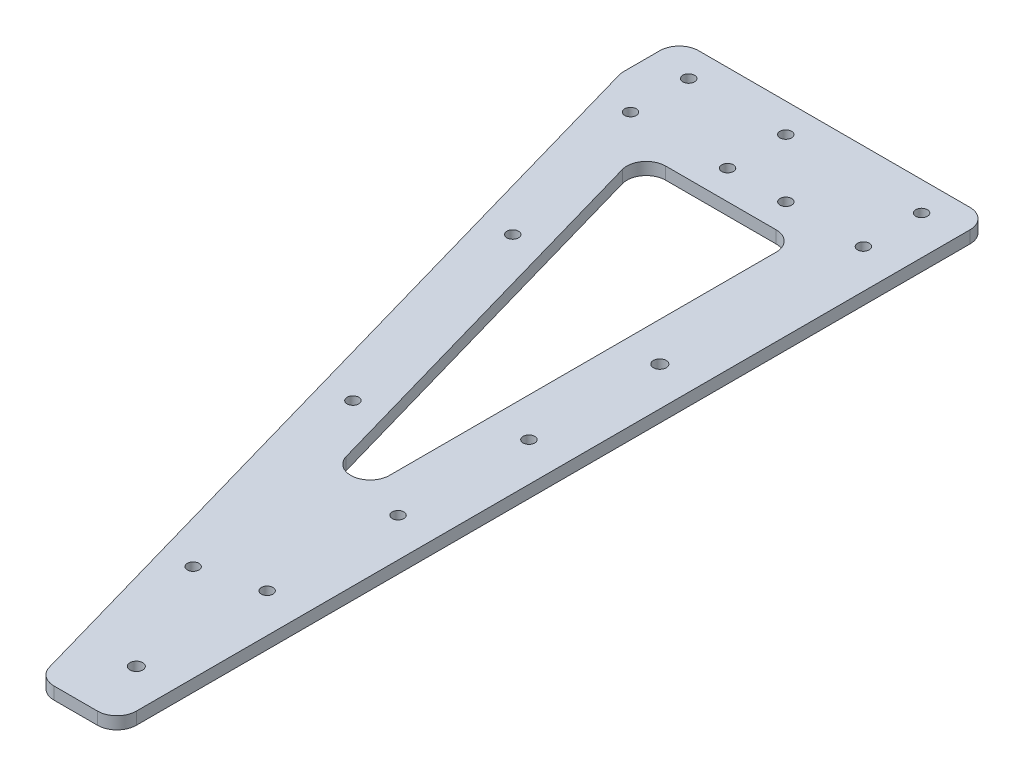
SolidWorks part; units mm, degrees
ref_plane "Front" through (0, 0, 0) normal (0, 0, 1) x (1, 0, 0)
ref_plane "Top" through (0, 0, 0) normal (0, 1, 0) x (1, 0, 0)
ref_plane "Right" through (0, 0, 0) normal (1, 0, 0) x (0, 0, -1)
sketch "Sketch1" plane through (0, 0, 0) normal (0, 1, 0) x (1, 0, 0)
  line L0 (-20, -210) -> (-80, 0)
  line L1 (0, 0) -> (-20, 0)
  line L2 (0, 0) -> (0, -210)
  line L3 (0, -210) -> (-20, -210)
  line L4 (-20, 0) -> (-20, -210)
  line L5 (-80, 0) -> (-20, 0)
  line L6 (-10, -210) -> (-10, -195)
  line L7 (-10, -195) -> (-10, -60)
  line L8 (-12.7886, -207.9396) -> (-70.057, -7.5)
  line L9 (-70.057, -7.5) -> (-20, -7.5)
  line L10 (-5.5771, -205.8792) -> (-60.1141, -15)
  line L11 (-60.1141, -15) -> (-20, -15)
  circle A0 centre (-10, -195) radius 1.65
  circle A1 centre (-10, -60) radius 1.65
  circle A2 centre (-70.057, -7.5) radius 1.5
  circle A3 centre (-45.0285, -7.5) radius 1.5
  circle A5 centre (-10, -127.5) radius 1500
  circle A6 centre (-10, -7.5) radius 1.5
  circle A7 centre (-10, -127.5) radius 1.5
  circle A8 centre (-10, -161.25) radius 1.5
  circle A9 centre (-10, -93.75) radius 1.5
  circle A10 centre (-41.4228, -107.7198) radius 1.5
  circle A11 centre (-57.9061, -50.0284) radius 1.5
  circle A12 centre (-24.9395, -165.4112) radius 1.5
  circle A13 centre (-30, -7.5) radius 1.5
  dimension "D6" = 7.5
  dimension "D7" = 33.75
  dimension "D10" = 60
  dimension "D1" = 20
  dimension "D2" = 210
  dimension "D3" = 60
  dimension "D4" = 15
  dimension "D5" = 135
  dimension "D8" = 33.75
  dimension "D11" = 60
  dimension "D12" = 10
  dimension "D9" = 15
extrude "Boss-Extrude1" add sketch "Sketch1" along normal blind 3.175
sketch "Sketch2" plane through (0, 0, 0) normal (0, -1, 0) x (1, 0, 0)
  line L0 (-80, 0) -> (0, 0)
  line L1 (-80, 0) -> (-80, -15)
  line L2 (0, 0) -> (0, -15)
  line L3 (-80, -15) -> (0, -15)
  line L4 (-70.057, 7.5) -> (-70.057, -7.5)
  line L5 (-45.0285, 7.5) -> (-45.0285, -7.5)
  line L6 (-10, 7.5) -> (-10, -7.5)
  circle A0 centre (-70.057, -7.5) radius 1.5
  circle A1 centre (-45.0285, -7.5) radius 1.5
  circle A2 centre (-10, -7.5) radius 1.5
  dimension "D1" = 15
  dimension "D2" = 15
  dimension "D3" = 15
  dimension "D4" = 15
extrude "Boss-Extrude2" add sketch "Sketch2" against normal blind 3.175
fillet "Fillet1" radius 5 8 edges at (-20, 1.5875, 155.3992) (-20, 1.5875, 15) (-60.1141, 1.5875, 15) (-80, 1.5875, -15) (0, 1.5875, -15) (0, 1.5875, 210) (-20, 1.5875, 210) (-80, 1.5875, 0)
